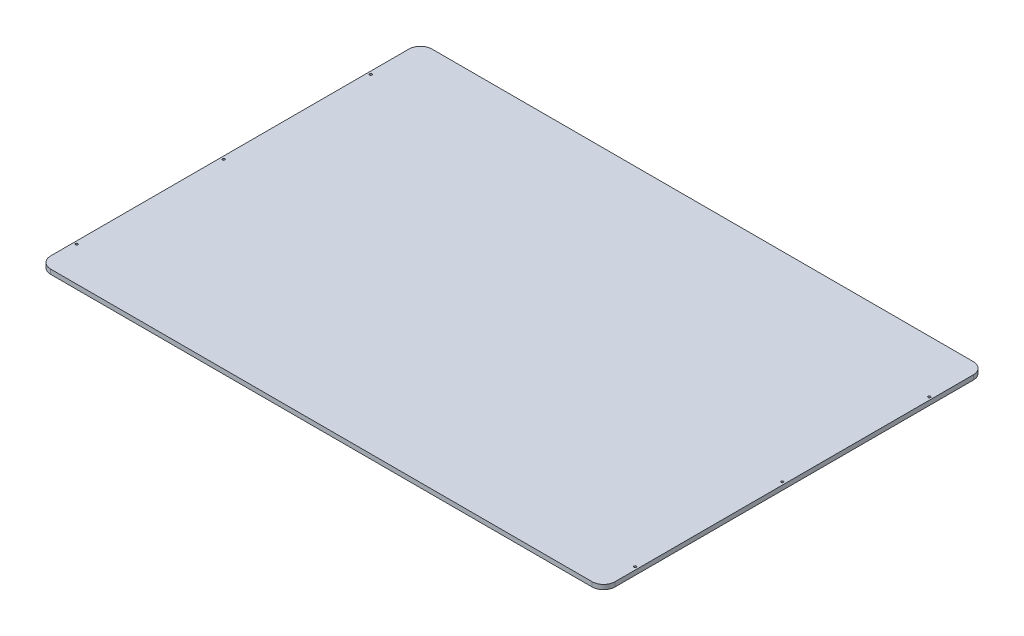
SolidWorks part; units mm, degrees
material "PMMA"
ref_plane "Front Plane" through (0, 0, 0) normal (0, 0, 1) x (1, 0, 0)
ref_plane "Top Plane" through (0, 0, 0) normal (0, 1, 0) x (1, 0, 0)
ref_plane "Right Plane" through (0, 0, 0) normal (1, 0, 0) x (0, 0, -1)
sketch "Sketch1" plane through (0, 0, 0) normal (0, 1, 0) x (1, 0, 0)
  line L1 (245, -165.5) -> (-245, -165.5)
  line L2 (245, -165.5) -> (245, 165.5)
  line L3 (245, 165.5) -> (-245, 165.5)
  line L4 (-245, -165.5) -> (-245, 165.5)
  line L5 (245, -165.5) -> (-245, 165.5) construction
  line L6 (245, 165.5) -> (-245, -165.5) construction
  point P0 (0, 0)
  dimension "D1" = 490
  dimension "D2" = 331
extrude "Boss-Extrude1" add sketch "Sketch1" along normal blind 4
sketch "Sketch2" plane through (0, 4, 0) normal (0, 1, 0) x (1, 0, 0)
  line L0 (-245, 165.5) -> (-245, -165.5) construction
  line L1 (-240, 135.5) -> (-235, 135.5)
  line L2 (-240, 135.5) -> (-240, 124.14)
  line L3 (-240, 124.14) -> (-235, 124.14)
  line L4 (-235, 135.5) -> (-235, 124.14)
  line L5 (245, 165.5) -> (-245, 165.5) construction
  dimension "D1" = 5
  dimension "D2" = 30
  dimension "D3" = 11.36
  dimension "D4" = 5
extrude "Cut-Extrude1" [suppressed] cut sketch "Sketch2" against normal through all
fillet "Fillet1" radius 10 4 edges at (245, 2, 165.5) (-245, 2, 165.5) (245, 2, -165.5) (-245, 2, -165.5)
pattern_linear "LPattern1" [suppressed] count 4 spacing 123.88
mirror "Mirror1" [suppressed] about plane through (0, 0, 0) normal (1, 0, 0)
hole_wizard "Tap Drill for M2.5x0.45 Tap1" positions "Sketch3" profile "Sketch4" hole size "M2.5x0.45" standard "ANSI Metric"
sketch "Sketch3" plane through (0, 0, 0) normal (0, -1, 0) x (-1, 0, 0)
  line L0 (235, -165.5) -> (-235, -165.5) construction
  line L1 (245, 155.5) -> (245, -155.5) construction
  point P0 (242.5, -135.5)
  dimension "D1" = 30
  dimension "D2" = 2.5
sketch "Sketch4" plane through (-242.5, 0, 135.5) normal (1, 0, 0) x (0, 0, -1)
  line L0 (0, 0) -> (0, 5.6159)
  line L1 (0, 5.6159) -> (1.025, 5)
  line L2 (1.025, 5) -> (1.025, 0)
  line L5 (1.025, 0) -> (0, 0)
  line L10 (0, 5.6159) -> (-1.025, 5) construction
  line L11 (0, -6.35) -> (0, 107.95) construction
  dimension "Hole Dia." = 2.05
  dimension "Hole Depth" = 5
  dimension "Drill Angle" = 118
pattern_linear "LPattern2" count 3 spacing 127.67 along (0, 0, -1) of "Tap Drill for M2.5x0.45 Tap1"
mirror "Mirror2" about plane through (0, 0, 0) normal (1, 0, 0) of "Tap Drill for M2.5x0.45 Tap1", "LPattern2"
other "Freeze***"
